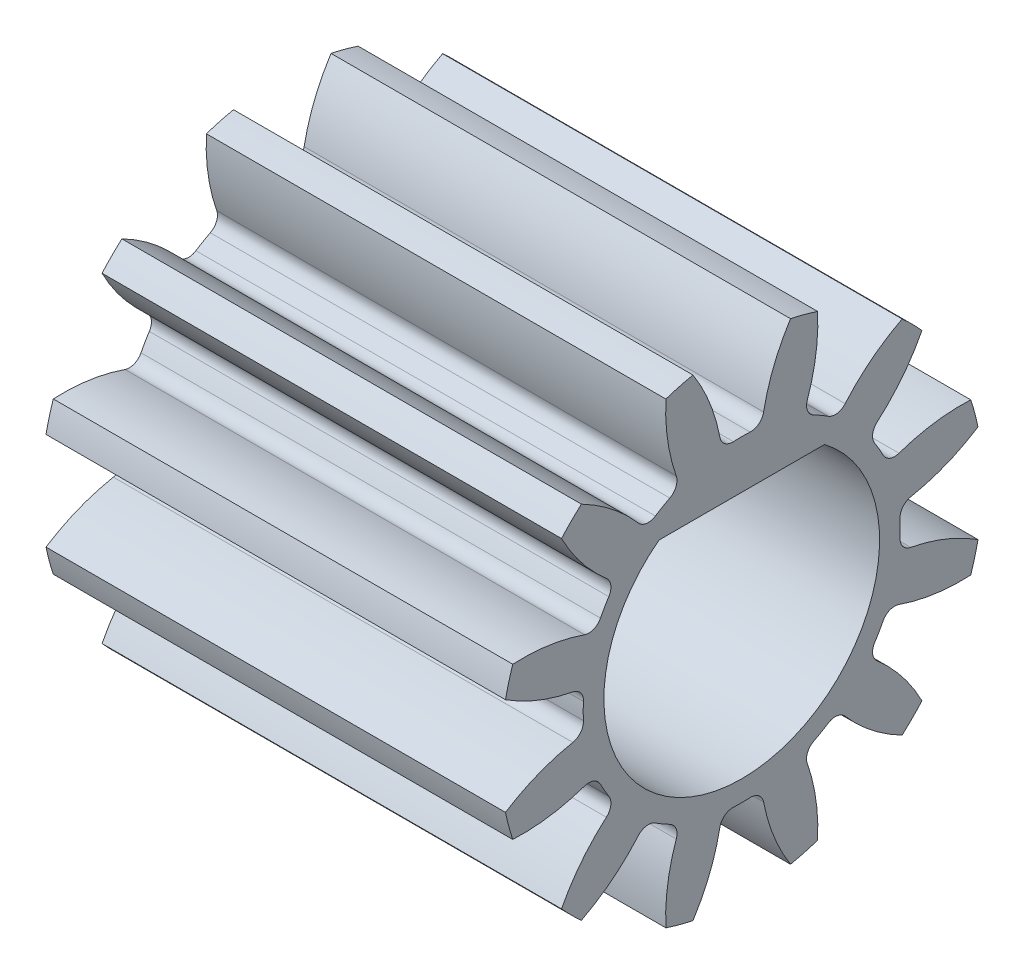
SolidWorks part; units mm, degrees
ref_plane "Front Plane" through (0, 0, 0) normal (0, 0, 1) x (1, 0, 0)
ref_plane "Top Plane" through (0, 0, 0) normal (0, 1, 0) x (1, 0, 0)
ref_plane "Right Plane" through (0, 0, 0) normal (1, 0, 0) x (0, 0, -1)
sketch "Sketch1" plane through (0, 0, 0) normal (1, 0, 0) x (0, 0, -1)
  circle A0 centre (0, 0) radius 3
  circle A1 centre (0, 0) radius 5.25
  dimension "D1" = 6
  dimension "D2" = 10.5
extrude "Boss-Extrude2" add sketch "Sketch1" along normal blind 10
sketch "Sketch3" plane through (10, 0, 0) normal (1, 0, 0) x (0, 0, -1)
  line L0 (0, 0) -> (0, 5.25) construction
  line L1 (-0.4357, 3.4224) -> (0, 0) construction
  line L2 (0, 2.5241) -> (-5.36, 17.2505) construction
  circle A0 centre (0, 0) radius 5.25 construction
  arc A1 (0.4357, 3.4224) -> (-0.4357, 3.4224) centre (0, 0) ccw
  arc A2 (0.7015, 4.445) -> (-0.7015, 4.445) centre (0, 0) ccw construction
  arc A3 (1.0614, 5.1416) -> (-1.0614, 5.1416) centre (0, 0) ccw
  arc A4 (-1.0614, 5.1416) -> (-0.4357, 3.4224) centre (-4.5489, 2.8988) cw
  arc A5 (1.0614, 5.1416) -> (0.4357, 3.4224) centre (4.5489, 2.8988) ccw
  point P17 (-0.6525, 4.3169)
  dimension "D1" = 10.5
  dimension "D2" = 9
  dimension "D3" = 1.8
  dimension "D4" = 20
  dimension "D5" = 1.4031
extrude "Cut-Extrude1" cut sketch "Sketch3" against normal through all
fillet "Fillet1" radius 0.285 2 edges at (5, 3.4224, -0.4357) (5, 3.4224, 0.4357)
pattern_circular "CirPattern2" count 12 over 360 about axis through (0, 0, 0) along (1, 0, 0) of "Fillet1", "Cut-Extrude1"
sketch "Sketch4" plane through (0, 0, 0) normal (-1, 0, 0) x (0, 0, 1)
  line L0 (0, -3) -> (3, -3) construction
  line L5 (-1.8, 2.4) -> (1.8, 2.4)
  circle A0 centre (0, 0) radius 3 construction
  arc A1 (-1.8, 2.4) -> (1.8, 2.4) centre (0, 0) cw
  dimension "D2" = 3
  dimension "D1" = 5.4
  dimension "D3" = 3.6
extrude "Boss-Extrude3" add sketch "Sketch4" against normal blind 10
equation "\"No of teeth\"= 12"
equation "\"Module\"= .75"
equation "\"Outer Diameter\"= ( \"No of teeth\" + 2 ) * \"Module\""
equation "\"Pitch Diameter\"= \"No of teeth\" * \"Module\""
equation "\"Backlash\"= 0.3 * \"Module\""
equation "\"Arc Length\"= ( ( \"Module\" * pi ) / 2 ) + \"Backlash\""
equation "\"Fillet Radius\"= 0.38 * \"Module\""
equation "\"Bore Diameter\"= 6"
equation "\"Presseure angle\"= 20"
equation "\"Tooth Design\"= IIF ( \"Module\" <= 1.25 , 2.4 * \"Module\" , 2.25 * \"Module\" )"
equation "\"D1@Sketch1\"=\"Bore Diameter\""
equation "\"D2@Sketch1\"=\"Outer Diameter\""
equation "\"D1@Sketch3\"=\"Outer Diameter\""
equation "\"D2@Sketch3\"=\"Pitch Diameter\""
equation "\"D3@Sketch3\"=\"Tooth Design\""
equation "\"D4@Sketch3\"=\"Presseure angle\""
equation "\"D5@Sketch3\"=\"Arc Length\""
equation "\"D1@Fillet1\"=\"Fillet Radius\""
equation "\"D1@CirPattern2\"=\"No of teeth\""
